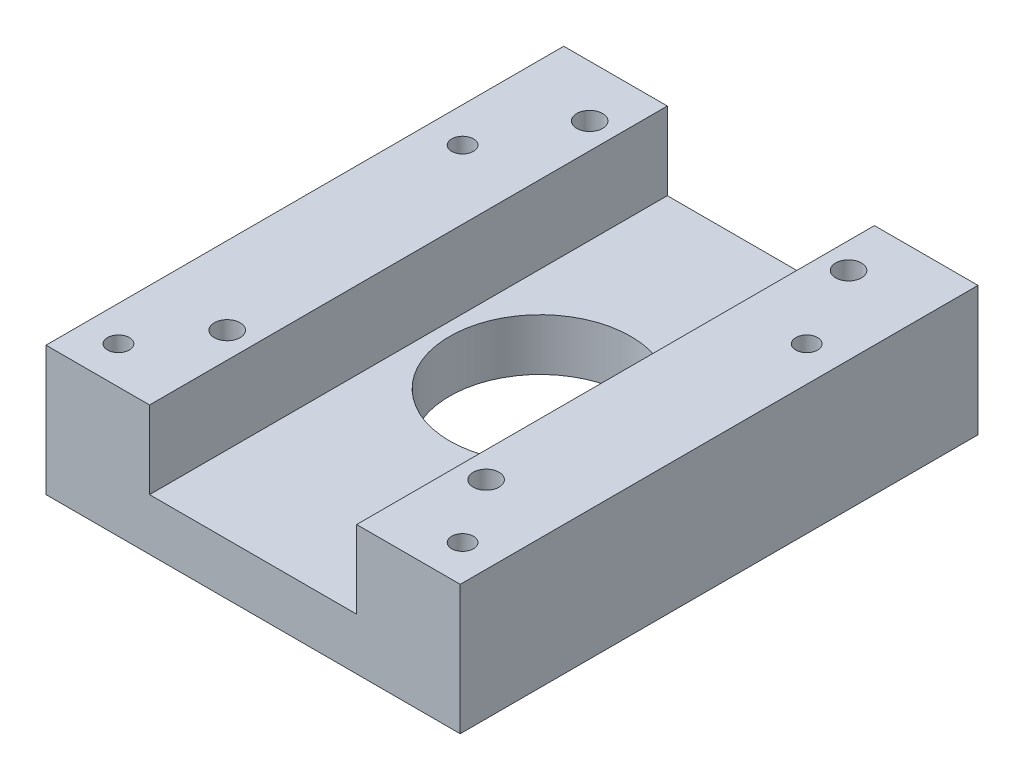
SolidWorks part; units mm, degrees
ref_plane "前视基准面" through (0, 0, 0) normal (0, 0, 1) x (1, 0, 0)
ref_plane "上视基准面" through (0, 0, 0) normal (0, 1, 0) x (1, 0, 0)
ref_plane "右视基准面" through (0, 0, 0) normal (1, 0, 0) x (0, 0, -1)
sketch "草图1" plane through (0, 0, 0) normal (0, 0, 1) x (1, 0, 0)
  line L0 (0, 0) -> (80, 0)
  line L1 (80, 0) -> (80, 25)
  line L2 (80, 25) -> (60, 25)
  line L3 (60, 25) -> (60, 10)
  line L4 (60, 10) -> (20, 10)
  line L5 (20, 10) -> (20, 25)
  line L6 (20, 25) -> (0, 25)
  line L7 (0, 25) -> (0, 0)
  dimension "D1" = 80
  dimension "D2" = 25
  dimension "D3" = 40
  dimension "D4" = 15
extrude "拉伸1" add sketch "草图1" along normal blind 80
sketch "草图2" plane through (0, 0, 0) normal (0, 1, 0) x (1, 0, 0)
  line L2 (0, -80) -> (80, -80) construction
  line L3 (0, -80) -> (0, 0) construction
  circle A2 centre (40, -24.55) radius 17.5
  dimension "D1" = 55.45
  dimension "D3" = 35
  dimension "D2" = 40
sketch "草图7" plane through (0, 0, 0) normal (0, 0, -1) x (-1, 0, 0)
  line L0 (-80, 0) -> (-80, 25)
  line L1 (-80, 25) -> (-60, 25)
  line L2 (-60, 25) -> (-60, 10)
  line L3 (-60, 10) -> (-20, 10)
  line L4 (-20, 10) -> (-20, 25)
  line L5 (-20, 25) -> (0, 25)
  line L6 (0, 25) -> (0, 0)
  line L7 (0, 0) -> (-80, 0)
extrude "拉伸4" add sketch "草图7" along normal blind 20
hole_wizard "M5 螺纹孔1" positions "3D草图1" profile "草图3" tap size "M5" standard "GB" end condition through all
sketch3d "3D草图1"
  circle A0 centre (73.234, -32, 72.7791) radius 3 construction
  circle A1 centre (73.234, -32, 72.7791) radius 3
  circle A2 centre (73.234, -32, 6.311) radius 3 construction
  circle A3 centre (73.234, -32, 6.311) radius 3
  circle A4 centre (6.766, -32, 72.7791) radius 3 construction
  circle A5 centre (6.766, -32, 72.7791) radius 3
  circle A6 centre (6.766, -32, 6.311) radius 3 construction
  circle A7 centre (6.766, -32, 6.311) radius 3
  point P0 (73.234, 0, 72.7791)
  point P2 (6.766, 0, 72.7791)
  point P4 (6.766, 0, 6.311)
  point P6 (73.234, 0, 6.311)
  point P11 (73.234, -29, 72.7791)
  point P13 (73.234, -29, 72.7791)
  point P16 (73.234, -29, 6.311)
  point P18 (73.234, -29, 6.311)
  point P21 (6.766, -29, 72.7791)
  point P23 (6.766, -29, 72.7791)
  point P26 (6.766, -29, 6.311)
  point P28 (6.766, -29, 6.311)
cosmetic thread "孔螺蚊线1" parameters "D2"=5
cosmetic thread "孔螺蚊线2" parameters "D2"=5
cosmetic thread "孔螺蚊线3" parameters "D2"=5
cosmetic thread "孔螺蚊线4" parameters "D2"=5
sketch "草图3" plane through (73.234, 0, 72.7791) normal (1, 0, 0) x (0, 0, -1)
  line L0 (0, 0) -> (0, 25)
  line L1 (0, 25) -> (2.1, 25)
  line L2 (2.1, 25) -> (2.1, 0)
  line L5 (2.1, 0) -> (0, 0)
  line L11 (0, -6.35) -> (0, 107.95) construction
  dimension "通孔螺纹孔钻头直径" = 4.2
  dimension "通孔螺纹孔钻头深度" = 25
hole_wizard "M6 螺纹孔1" positions "草图5" profile "草图4" tap size "M6" standard "GB" end condition through all
sketch "草图5" plane through (0, 25, 0) normal (0, 1, 0) x (-1, 0, 0)
  line L1 (0, 80) -> (0, -20) construction
  line L2 (-20, 80) -> (0, 80) construction
  point P0 (-15, -10)
  point P1 (-15, 60)
  point P3 (-65, -10)
  point P5 (-65, 60)
  dimension "D1" = 70
  dimension "D2" = 20
  dimension "D3" = 50
  dimension "D4" = 15
cosmetic thread "孔螺蚊线5" parameters "D2"=6
cosmetic thread "孔螺蚊线6" parameters "D2"=6
cosmetic thread "孔螺蚊线7" parameters "D2"=6
cosmetic thread "孔螺蚊线8" parameters "D2"=6
sketch "草图4" plane through (15, 25, -10) normal (1, 0, 0) x (0, 0, 1)
  line L0 (0, 0) -> (0, 25)
  line L1 (0, 25) -> (2.5, 25)
  line L2 (2.5, 25) -> (2.5, 0)
  line L5 (2.5, 0) -> (0, 0)
  line L11 (0, -6.35) -> (0, 107.95) construction
  dimension "通孔螺纹孔钻头直径" = 5
  dimension "通孔螺纹孔钻头深度" = 25
extrude "拉伸2" cut sketch "草图2" along normal through all
